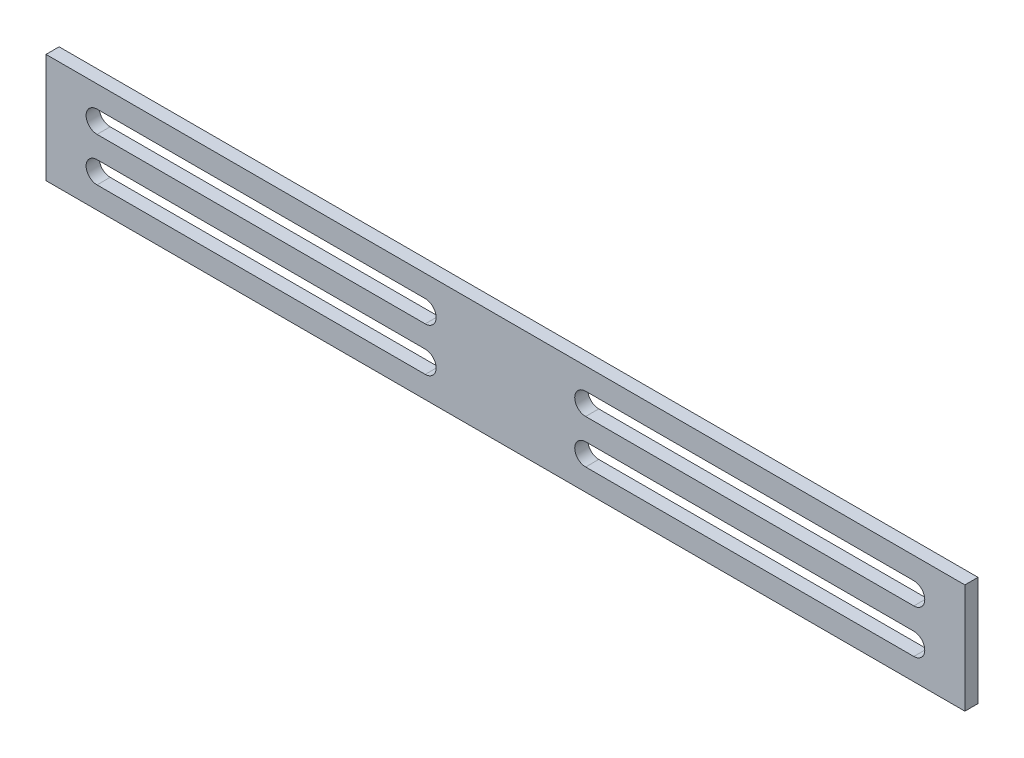
SolidWorks part; units mm, degrees
ref_plane "Plano frontal" through (0, 0, 0) normal (0, 0, 1) x (1, 0, 0)
ref_plane "Plano superior" through (0, 0, 0) normal (0, 1, 0) x (1, 0, 0)
ref_plane "Plano direito" through (0, 0, 0) normal (1, 0, 0) x (0, 0, -1)
sketch "Esboço1" plane through (0, 0, 0) normal (0, 0, 1) x (1, 0, 0)
  line L1 (-63, -7.5) -> (63, -7.5)
  line L2 (-63, -7.5) -> (-63, 7.5)
  line L3 (-63, 7.5) -> (63, 7.5)
  line L4 (63, -7.5) -> (63, 7.5)
  line L5 (-63, -7.5) -> (63, 7.5) construction
  line L6 (-63, 7.5) -> (63, -7.5) construction
  point P0 (0, 0)
  dimension "D1" = 126
  dimension "D2" = 15
extrude "Ressalto-extrusão1" add sketch "Esboço1" along normal blind 1.8
sketch "Esboço2" plane through (0, 0, 1.8) normal (0, 0, 1) x (1, 0, 0)
  line L0 (0, -7.5) -> (0, 7.5) construction
  line L1 (-63, -7.5) -> (63, -7.5) construction
  line L2 (63, 7.5) -> (-63, 7.5) construction
  line L3 (63, 0) -> (-63, 0) construction
  line L4 (63, -7.5) -> (63, 7.5) construction
  line L5 (-63, 7.5) -> (-63, -7.5) construction
  line L6 (-56, 3) -> (-11, 3) construction
  line L7 (-56, 4.5) -> (-11, 4.5)
  line L8 (-56, 1.5) -> (-11, 1.5)
  line L9 (-56, -3) -> (-11, -3) construction
  line L10 (-56, -4.5) -> (-11, -4.5)
  line L11 (-56, -1.5) -> (-11, -1.5)
  line L12 (56, -3) -> (11, -3) construction
  line L13 (56, -4.5) -> (11, -4.5)
  line L14 (56, -1.5) -> (11, -1.5)
  line L15 (56, 3) -> (11, 3) construction
  line L16 (56, 4.5) -> (11, 4.5)
  line L17 (56, 1.5) -> (11, 1.5)
  arc A0 (-56, 4.5) -> (-56, 1.5) centre (-56, 3) ccw
  arc A1 (-11, 1.5) -> (-11, 4.5) centre (-11, 3) ccw
  arc A2 (-56, -4.5) -> (-56, -1.5) centre (-56, -3) cw
  arc A3 (-11, -1.5) -> (-11, -4.5) centre (-11, -3) cw
  arc A4 (56, -4.5) -> (56, -1.5) centre (56, -3) ccw
  arc A5 (11, -1.5) -> (11, -4.5) centre (11, -3) ccw
  arc A6 (56, 4.5) -> (56, 1.5) centre (56, 3) cw
  arc A7 (11, 1.5) -> (11, 4.5) centre (11, 3) cw
  point P14 (-33.5, 3)
  point P22 (-33.5, -3)
  point P29 (33.5, -3)
  point P36 (33.5, 3)
  dimension "D4" = 7
  dimension "D1" = 45
  dimension "D2" = 3
  dimension "D3" = 3
extrude "Corte-extrusão1" cut sketch "Esboço2" against normal through all
